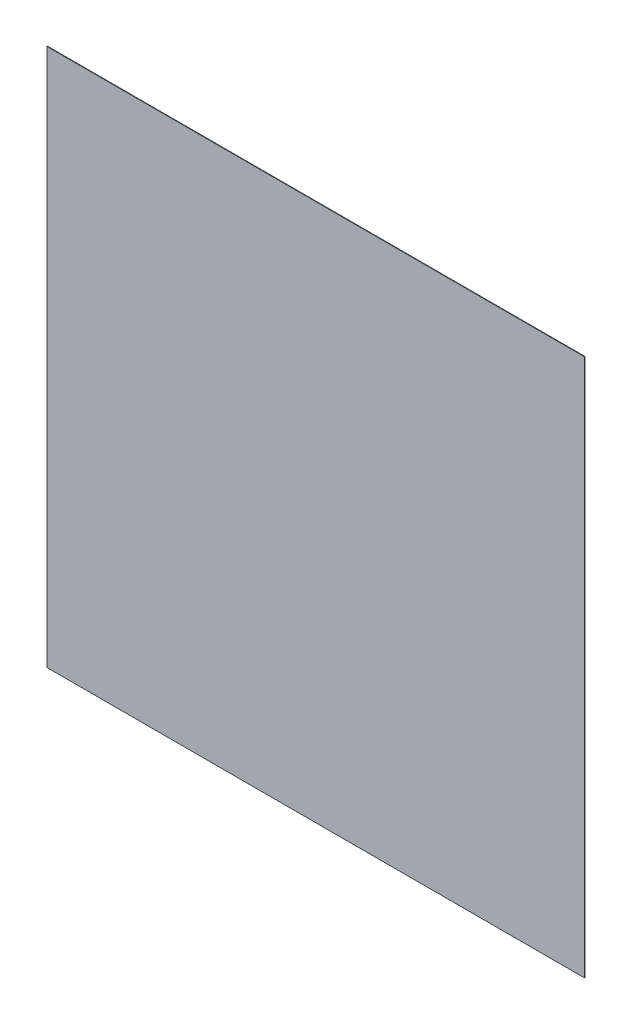
SolidWorks part; units mm, degrees
ref_plane "前视基准面" through (0, 0, 0) normal (0, 0, 1) x (1, 0, 0)
ref_plane "上视基准面" through (0, 0, 0) normal (0, 1, 0) x (1, 0, 0)
ref_plane "右视基准面" through (0, 0, 0) normal (1, 0, 0) x (0, 0, -1)
sketch "草图1" plane through (0, 0, 0) normal (0, 0, 1) x (1, 0, 0)
  line L1 (0, 0) -> (1000, 0)
  line L2 (0, 0) -> (0, -1000)
  line L3 (0, -1000) -> (1000, -1000)
  line L4 (1000, 0) -> (1000, -1000)
  dimension "D1" = 1000
  dimension "D2" = 1000
extrude "凸台-拉伸1" add sketch "草图1" along normal blind 1
